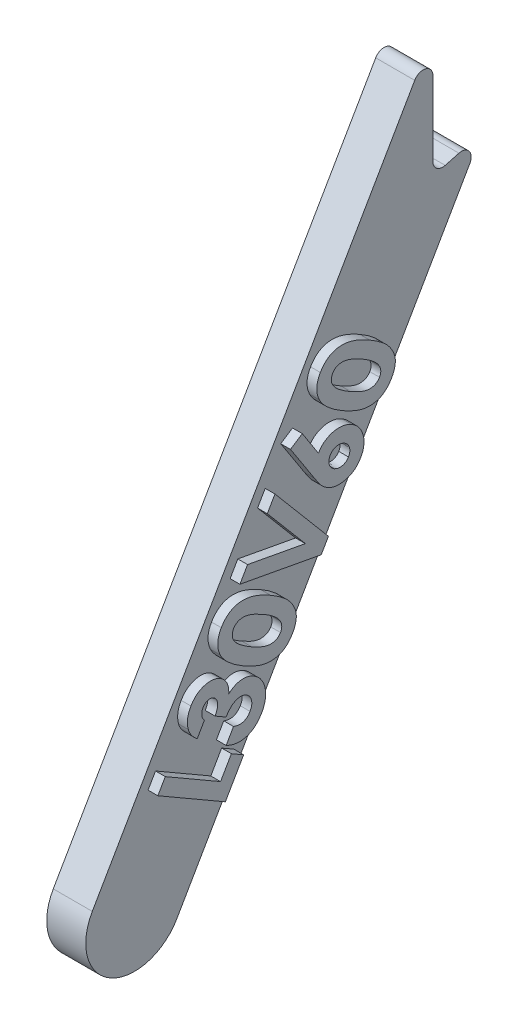
SolidWorks part; units mm, degrees
ref_plane "Front Plane" through (0, 0, 0) normal (0, 0, 1) x (1, 0, 0)
ref_plane "Top Plane" through (0, 0, 0) normal (0, 1, 0) x (1, 0, 0)
ref_plane "Right Plane" through (0, 0, 0) normal (1, 0, 0) x (0, 0, -1)
sketch "Sketch1" plane through (0, 0, 0) normal (1, 0, 0) x (0, 0, -1)
  line L0 (-2.1651, 1.25) -> (15.297, 31.4952)
  line L1 (15.297, 31.4952) -> (15.297, 25.807)
  line L3 (17.797, 25.8252) -> (2.1651, -1.25)
  line L4 (0, 0) -> (8.6736, 0) construction
  line L7 (15.9264, 25.324) -> (17.797, 25.8252)
  arc A0 (-2.1651, 1.25) -> (2.1651, -1.25) centre (0, 0) ccw
  arc A1 (15.297, 25.807) -> (15.9264, 25.324) centre (15.797, 25.807) ccw
  dimension "D5" = 0.5
  dimension "D1" = 2
  dimension "D3" = 30
  dimension "D4" = 60
  dimension "D6" = 45
  dimension "D7" = 5
extrude "Boss-Extrude1" add sketch "Sketch1" along normal blind 2
fillet "Fillet1" radius 0.5 2 edges at (1, 31.4952, -15.297) (1, 25.8252, -17.797)
sketch "Sketch2" plane through (2, 0, 0) normal (1, 0, 0) x (0, 0, -1)
  line L0 (3.5967, 2.2296) -> (13.5967, 19.5501) construction
  line L1 (2.1651, -1.25) -> (17.1934, 24.7798) construction
  text T0 "L30V60" font "Century Gothic" height 4
  point P5 (4.0297, 1.9796)
  dimension "D1" = 0.5
  dimension "D2" = 20
extrude "Boss-Extrude2" add sketch "Sketch2" along normal blind 0.5
